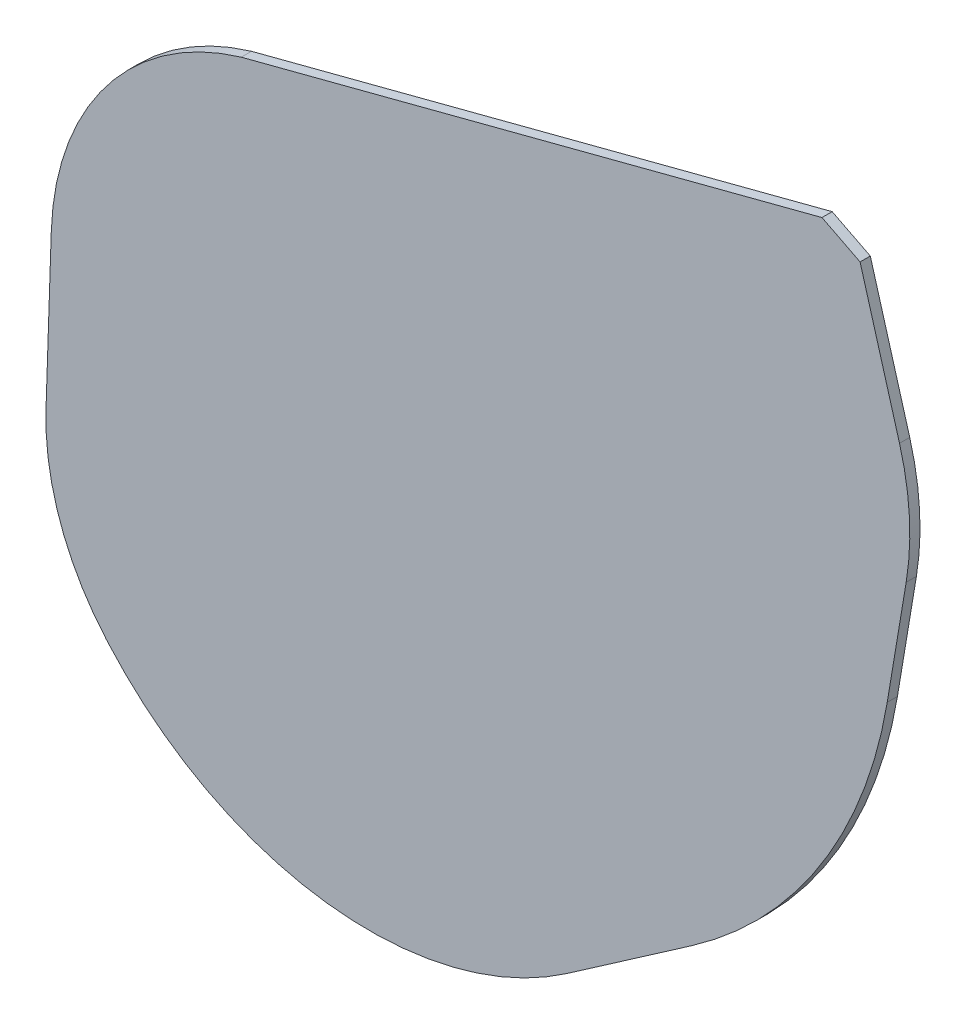
SolidWorks part; units mm, degrees
ref_plane "Front Plane" through (0, 0, 0) normal (0, 0, 1) x (1, 0, 0)
ref_plane "Top Plane" through (0, 0, 0) normal (0, 1, 0) x (1, 0, 0)
ref_plane "Right Plane" through (0, 0, 0) normal (1, 0, 0) x (0, 0, -1)
sketch "Sketch2" plane through (0, 0, 0) normal (0, 0, 1) x (1, 0, 0)
  line L0 (77.6667, 150) -> (388.3333, 150) construction
  line L1 (52.4805, 258.675) -> (196.8948, 296.3428)
  line L3 (217.8369, 228.2504) -> (213.1205, 200.0364)
  line L4 (164.4487, 123.2792) -> (133.5605, 101.8652)
  line L5 (19.3436, 115.9934) -> (18.9488, 116.4449)
  line L6 (3.9153, 158.621) -> (5.2264, 197.5738)
  line L7 (196.8948, 296.3428) -> (206.3731, 291.5239)
  line L8 (206.3731, 291.5239) -> (216.1786, 257.3555)
  arc A0 (52.4805, 258.675) -> (5.2264, 197.5738) centre (71.2291, 195.3522) ccw
  arc A1 (216.1786, 257.3555) -> (217.8369, 228.2504) centre (152.7008, 239.1389) cw
  arc A2 (213.1205, 200.0364) -> (164.4487, 123.2792) centre (97.8796, 219.3007) cw
  arc A3 (133.5605, 101.8652) -> (19.3436, 115.9934) centre (84.3573, 172.8377) cw
  arc A4 (18.9488, 116.4449) -> (3.9153, 158.621) centre (64.8408, 156.5703) cw
  dimension "D1" = 66.04
  dimension "D4" = 86.36
  dimension "D5" = 60.96
extrude "Boss-Extrude1" add sketch "Sketch2" along normal blind 2.54
